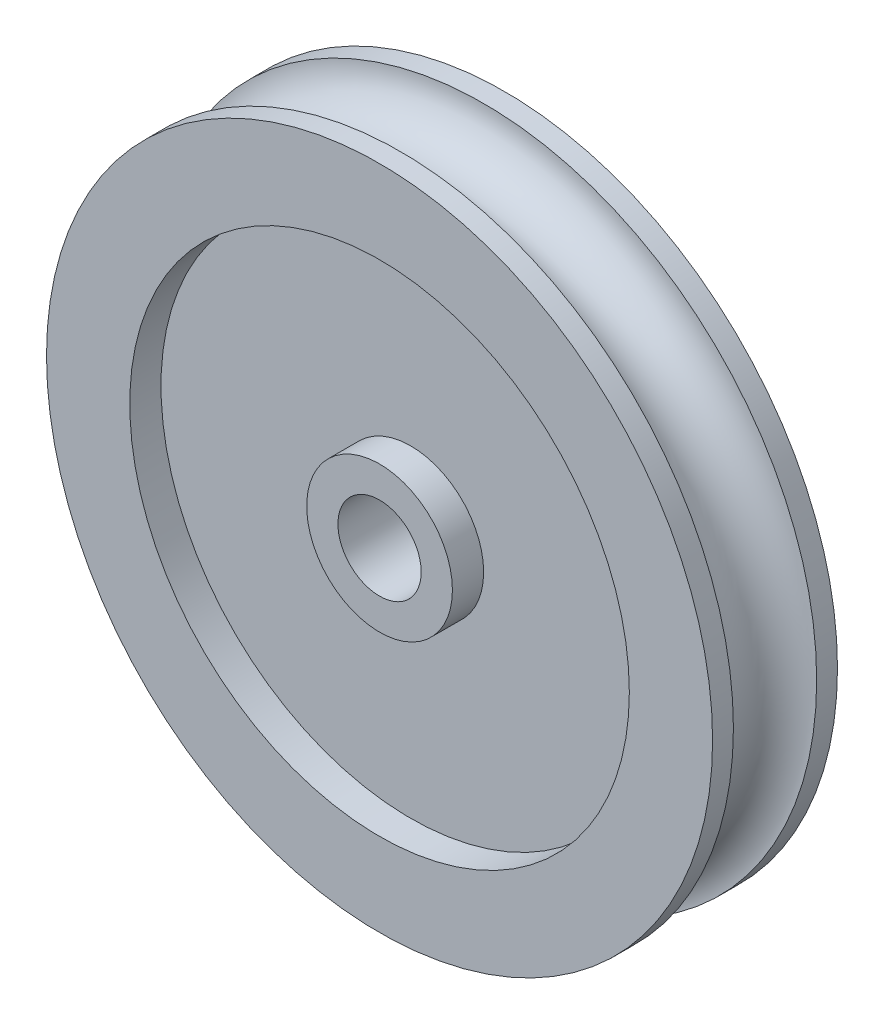
SolidWorks part; units mm, degrees
material "2.0375 (CuZn36Pb3)"
ref_plane "Front Plane" through (0, 0, 0) normal (0, 0, 1) x (1, 0, 0)
ref_plane "Top Plane" through (0, 0, 0) normal (0, 1, 0) x (1, 0, 0)
ref_plane "Right Plane" through (0, 0, 0) normal (1, 0, 0) x (0, 0, -1)
sketch "Sketch1" plane through (0, 0, 0) normal (1, 0, 0) x (0, 0, -1)
  line L0 (0, 51.1769) -> (0, -54.1224) construction
  line L1 (0, 55) -> (0, -55) construction
  line L2 (-9.525, 6.35) -> (9.525, 6.35)
  line L3 (9.525, 6.35) -> (9.525, 11.1125)
  line L4 (-9.525, 6.35) -> (-9.525, 11.1125)
  line L5 (9.525, 11.1125) -> (4.7625, 11.1125)
  line L6 (-9.525, 11.1125) -> (-4.7625, 11.1125)
  line L7 (4.7625, 11.1125) -> (4.7625, 38.1)
  line L8 (-4.7625, 11.1125) -> (-4.7625, 38.1)
  line L9 (4.7625, 38.1) -> (9.525, 38.1)
  line L10 (-4.7625, 38.1) -> (-9.525, 38.1)
  line L11 (9.525, 38.1) -> (9.525, 50.8)
  line L12 (-9.525, 38.1) -> (-9.525, 50.8)
  line L13 (9.525, 50.8) -> (6.35, 50.8)
  line L14 (-9.525, 50.8) -> (-6.35, 50.8)
  line L15 (55, 0) -> (-55, 0) construction
  line L16 (-17.8641, 0) -> (21.6831, 0) construction
  line L17 (17.8641, 0) -> (-21.6831, 0) construction
  arc A0 (-6.35, 50.8) -> (6.35, 50.8) centre (0, 50.8) ccw
  point P8 (0, 6.35)
  dimension "D9" = 6.35
  dimension "D1" = 6.35
  dimension "D2" = 4.7625
  dimension "D3" = 38.1
  dimension "D4" = 50.8
  dimension "D5" = 9.525
  dimension "D6" = 19.05
  dimension "D7" = 19.05
  dimension "D8" = 12.7
revolve "Revolve1" add sketch "Sketch1" angle 360 about L16
